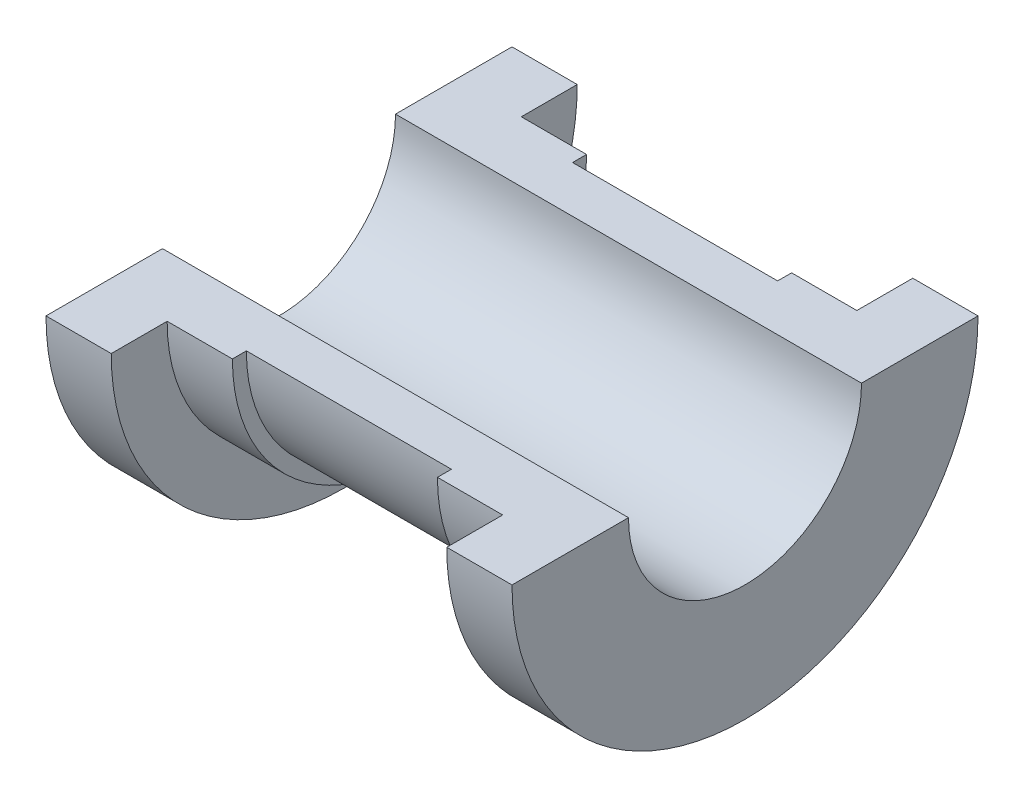
SolidWorks part; units mm, degrees
ref_plane "Front Plane" through (0, 0, 0) normal (0, 0, 1) x (1, 0, 0)
ref_plane "Top Plane" through (0, 0, 0) normal (0, 1, 0) x (1, 0, 0)
ref_plane "Right Plane" through (0, 0, 0) normal (1, 0, 0) x (0, 0, -1)
sketch "Sketch1" plane through (0, 0, 0) normal (0, 0, 1) x (1, 0, 0)
  line L0 (-25, 0) -> (25, 0)
  line L1 (25, 0) -> (25, 25)
  line L2 (25, 25) -> (18, 25)
  line L3 (18, 25) -> (18, 19)
  line L4 (18, 19) -> (11, 19)
  line L5 (11, 19) -> (11, 17.5)
  line L6 (11, 17.5) -> (-11, 17.5)
  line L8 (-11, 19) -> (-11, 17.5)
  line L9 (-18, 19) -> (-11, 19)
  line L10 (-18, 25) -> (-18, 19)
  line L11 (-25, 25) -> (-18, 25)
  line L12 (-25, 0) -> (-25, 25)
  dimension "D3" = 25
  dimension "D5" = 7
  dimension "D6" = 7
  dimension "D7" = 1.5
  dimension "D8" = 6
revolve "Revolve1" add sketch "Sketch1" angle 360 about L0
sketch "Sketch2" plane through (25, 0, 0) normal (1, 0, 0) x (0, 0, -1)
  circle A0 centre (0, 0) radius 12.5
extrude "Cut-Extrude1" cut sketch "Sketch2" against normal through all
sketch "Sketch3" plane through (25, 0, 0) normal (1, 0, 0) x (0, 0, -1)
  line L0 (-25, 0) -> (25, 0)
  circle A0 centre (0, 0) radius 25 construction
extrude "Cut-Extrude4" cut sketch "Sketch3" against normal through all and the other way through all
ref_plane "Plane2" through (0, -17.5, 0) normal (0, 1, 0) x (1, 0, 0)
sketch "Sketch5" plane through (0, -17.5, 0) normal (0, 1, 0) x (1, 0, 0)
  circle A0 centre (0, 0) radius 3
extrude "Boss-Extrude1" add sketch "Sketch5" against normal blind 5 separate body
